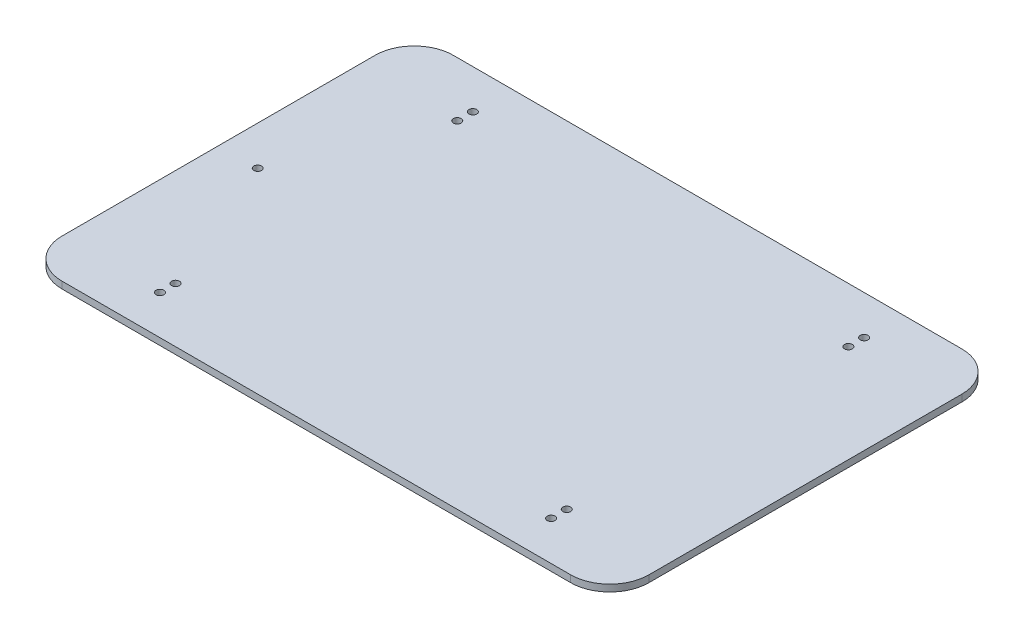
SolidWorks part; units mm, degrees
material "1060 Alloy"
ref_plane "Front Plane" through (0, 0, 0) normal (0, 0, 1) x (1, 0, 0)
ref_plane "Top Plane" through (0, 0, 0) normal (0, 1, 0) x (1, 0, 0)
ref_plane "Right Plane" through (0, 0, 0) normal (1, 0, 0) x (0, 0, -1)
sketch "Sketch1" plane through (0, 0, 0) normal (0, 1, 0) x (1, 0, 0)
  line L1 (130, -100) -> (-130, -100)
  line L2 (150, -80) -> (150, 80)
  line L3 (130, 100) -> (-130, 100)
  line L4 (-150, -80) -> (-150, 80)
  line L5 (100, -80) -> (-100, -80) construction
  line L6 (100, -80) -> (100, 80) construction
  line L7 (100, 80) -> (-100, 80) construction
  line L8 (-100, -80) -> (-100, 80) construction
  line L9 (100, -80) -> (-100, 80) construction
  line L10 (100, 80) -> (-100, -80) construction
  circle A0 centre (-100, 80) radius 2
  circle A1 centre (100, 80) radius 2
  circle A2 centre (100, -80) radius 2
  circle A3 centre (-100, -80) radius 2
  arc A4 (150, 80) -> (130, 100) centre (130, 80) ccw
  arc A5 (130, -100) -> (150, -80) centre (130, -80) ccw
  arc A6 (-130, -100) -> (-150, -80) centre (-130, -80) cw
  arc A7 (-130, 100) -> (-150, 80) centre (-130, 80) ccw
  circle A8 centre (-130, 0) radius 2
  point P0 (0, 0)
  point P6 (-150, 0)
  point P7 (0, 0)
  point P18 (150, 100)
  point P23 (-150, -100)
  point P26 (-150, 100)
  dimension "D6" = 4
  dimension "D7" = 20
  dimension "D8" = 4
  dimension "D1" = 300
  dimension "D2" = 200
  dimension "D3" = 200
  dimension "D4" = 20
  dimension "D5" = 160
  dimension "D9" = 20
extrude "Boss-Extrude1" add sketch "Sketch1" along normal blind 3.5
sketch "Sketch3" plane through (0, 3.5, 0) normal (0, 1, 0) x (1, 0, 0)
  circle A0 centre (-100, 72) radius 2
  circle A1 centre (-100, 80) radius 2 construction
  circle A2 centre (-100, -72) radius 2
  circle A3 centre (100, -72) radius 2
  circle A4 centre (100, 72) radius 2
  dimension "D1" = 4
  dimension "D2" = 8
extrude "Cut-Extrude2" cut sketch "Sketch3" against normal blind 10
